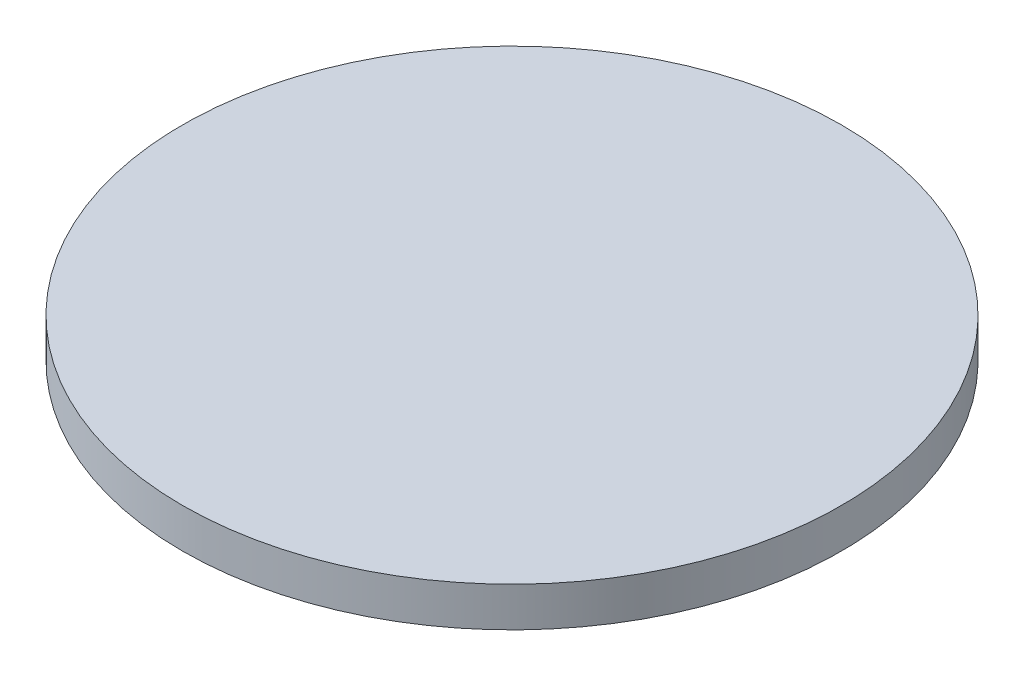
SolidWorks part; units mm, degrees
ref_plane "Front Plane" through (0, 0, 0) normal (0, 0, 1) x (1, 0, 0)
ref_plane "Top Plane" through (0, 0, 0) normal (0, 1, 0) x (1, 0, 0)
ref_plane "Right Plane" through (0, 0, 0) normal (1, 0, 0) x (0, 0, -1)
sketch "Sketch1" plane through (0, 0, 0) normal (0, 1, 0) x (1, 0, 0)
  circle A0 centre (0, 0) radius 12.5
  dimension "D1" = 25
extrude "Boss-Extrude1" add sketch "Sketch1" along normal blind 1.5
